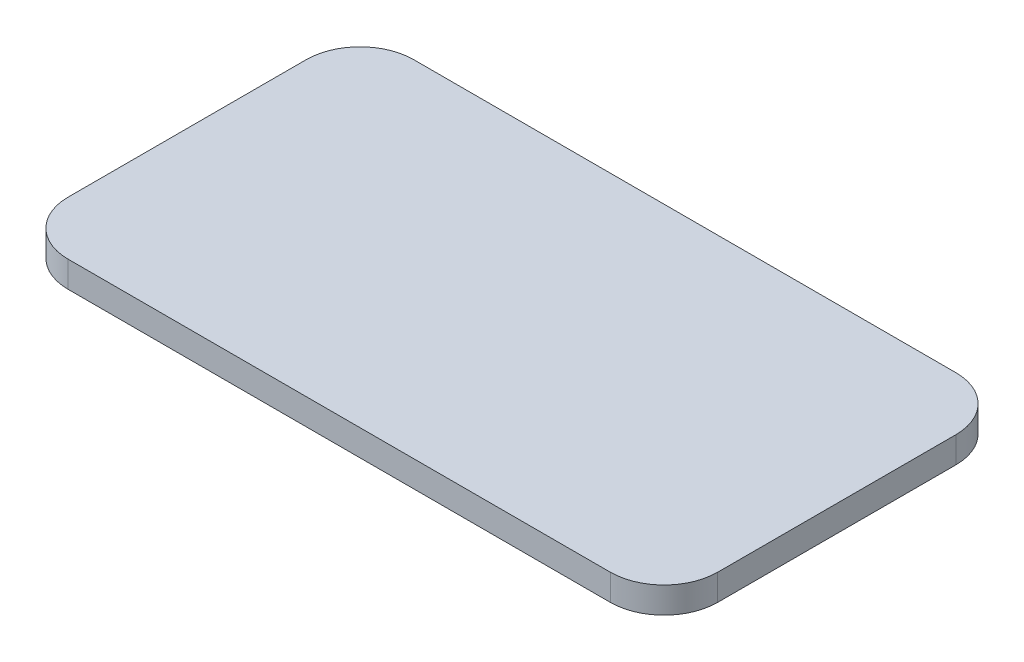
SolidWorks part; units mm, degrees
ref_plane "前视基准面" through (0, 0, 0) normal (0, 0, 1) x (1, 0, 0)
ref_plane "上视基准面" through (0, 0, 0) normal (0, 1, 0) x (1, 0, 0)
ref_plane "右视基准面" through (0, 0, 0) normal (1, 0, 0) x (0, 0, -1)
other "Configuration Table"
sketch "草图1" plane through (0, 0, 0) normal (0, 1, 0) x (1, 0, 0)
  line L1 (0, 0) -> (36.28, 0)
  line L2 (0, 0) -> (0, 19.3)
  line L3 (0, 19.3) -> (36.28, 19.3)
  line L4 (36.28, 0) -> (36.28, 19.3)
  line L5 (0, 0) -> (36.28, 19.3) construction
  line L6 (0, 19.3) -> (36.28, 0) construction
  point P4 (18.14, 9.65)
  dimension "D1" = 19.3
  dimension "D2" = 36.28
extrude "凸台-拉伸1" add sketch "草图1" along normal blind 1.46
fillet "圆角1" radius 3 4 edges at (0, 0.73, -19.3) (36.28, 0.73, -19.3) (36.28, 0.73, 0) (0, 0.73, 0)
